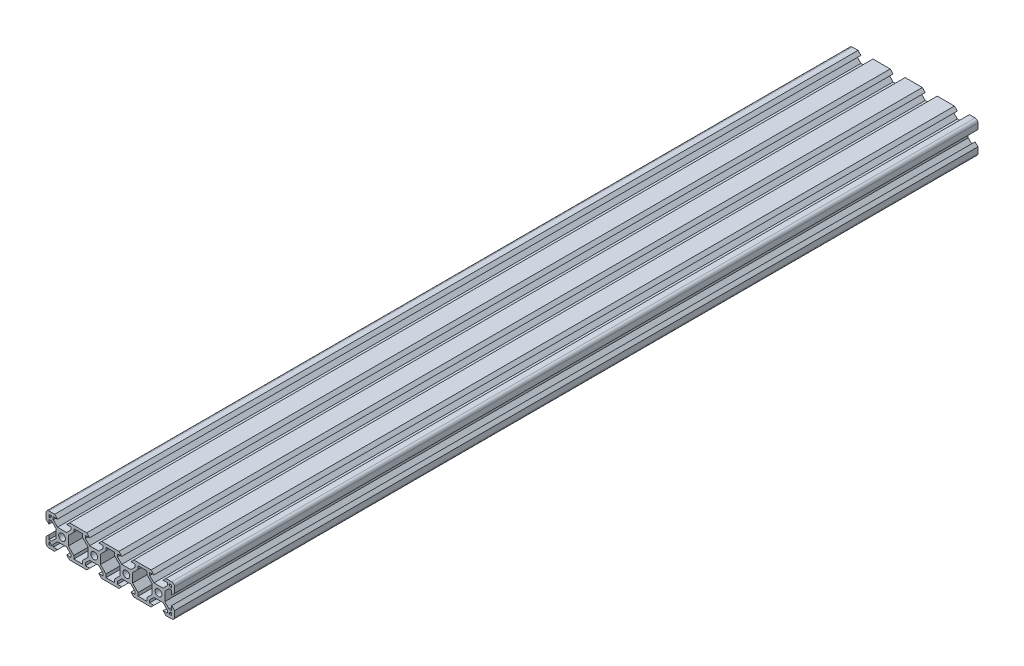
SolidWorks part; units mm, degrees
material "5052-H38, Barre (SS)"
ref_plane "Plan de face" through (0, 0, 0) normal (0, 0, 1) x (1, 0, 0)
ref_plane "Plan de dessus" through (0, 0, 0) normal (0, 1, 0) x (1, 0, 0)
ref_plane "Plan de droite" through (0, 0, 0) normal (1, 0, 0) x (0, 0, -1)
sketch "Esquisse1" plane through (0, 0, 0) normal (0, 0, 1) x (1, 0, 0)
  line L0 (0, 0) -> (0, 10) construction
  line L1 (0, 0) -> (-40, 0) construction
  line L2 (-40, 10) -> (-30, 0) construction
  line L3 (-30, 0) -> (-20, 10) construction
  line L4 (-20, 10) -> (-10, 0) construction
  line L5 (-10, 0) -> (0, 10) construction
  line L6 (-10, 0) -> (-10, 10) construction
  line L7 (-20, 10) -> (-20, 0) construction
  line L8 (-40, 0) -> (-40, 10) construction
  line L9 (-38.2, 10) -> (-34.64, 10)
  line L10 (-34.64, 10) -> (-32.84, 8.2)
  line L11 (-32.84, 8.2) -> (-35.4993, 8.2)
  line L12 (-35.4993, 8.2) -> (-35.4993, 6.56)
  line L13 (-35.4993, 6.56) -> (-32.84, 3.9007)
  line L14 (-32.84, 3.9007) -> (-27.16, 3.9007)
  line L15 (-30, 0) -> (-30, 10) construction
  line L16 (-33.9007, 2.84) -> (-33.9007, 0)
  line L17 (-36.56, 5.4993) -> (-33.9007, 2.84)
  line L18 (-38.2, 5.4993) -> (-36.56, 5.4993)
  line L19 (-38.2, 2.84) -> (-38.2, 5.4993)
  line L20 (-40, 4.64) -> (-38.2, 2.84)
  line L21 (-40, 8.2) -> (-40, 4.64)
  line L22 (-38.2, 8.2) -> (-38.2, 6.5693)
  line L23 (-38.2, 6.5693) -> (-37.63, 6.5693)
  line L24 (-37.63, 6.5693) -> (-36.5693, 7.63)
  line L25 (-36.5693, 7.63) -> (-36.5693, 8.2)
  line L26 (-36.5693, 8.2) -> (-38.2, 8.2)
  line L27 (-17.3, 6.2393) -> (-17.3, 8.2)
  line L28 (-13.9007, 2.84) -> (-17.3, 6.2393)
  line L29 (-13.9007, -2.84) -> (-13.9007, 2.84)
  line L30 (-14.64, 10) -> (-12.84, 8.2)
  line L31 (-12.84, 8.2) -> (-15.4993, 8.2)
  line L32 (-15.4993, 8.2) -> (-15.4993, 6.56)
  line L33 (-15.4993, 6.56) -> (-12.84, 3.9007)
  line L34 (-12.84, 3.9007) -> (-7.16, 3.9007)
  line L35 (-5.36, 10) -> (-7.16, 8.2)
  line L36 (-7.16, 8.2) -> (-4.5007, 8.2)
  line L37 (-4.5007, 8.2) -> (-4.5007, 6.56)
  line L38 (-4.5007, 6.56) -> (-7.16, 3.9007)
  line L39 (-5.36, 10) -> (5.36, 10)
  line L40 (-6.0993, -2.84) -> (-6.0993, 2.84)
  line L41 (-6.0993, 2.84) -> (-2.7, 6.2393)
  line L42 (-2.7, 6.2393) -> (-2.7, 8.2)
  line L43 (-2.7, 8.2) -> (2.7, 8.2)
  line L44 (-25.36, 10) -> (-27.16, 8.2)
  line L45 (-7.16, 3.9007) -> (-6.0993, 2.84) construction
  line L46 (-36.5693, -7.63) -> (-36.5693, -8.2)
  line L47 (-37.63, -6.5693) -> (-36.5693, -7.63)
  line L48 (-38.2, -6.5693) -> (-37.63, -6.5693)
  line L49 (-38.2, -8.2) -> (-38.2, -6.5693)
  line L50 (-27.16, 8.2) -> (-24.5007, 8.2)
  line L51 (-24.5007, 8.2) -> (-24.5007, 6.56)
  line L52 (-24.5007, 6.56) -> (-27.16, 3.9007)
  line L53 (-25.36, 10) -> (-14.64, 10)
  line L54 (-26.0993, -2.84) -> (-26.0993, 2.84)
  line L55 (-26.0993, 2.84) -> (-22.7, 6.2393)
  line L56 (-22.7, 6.2393) -> (-22.7, 8.2)
  line L57 (-22.7, 8.2) -> (-17.3, 8.2)
  line L58 (-27.16, 3.9007) -> (-26.0993, 2.84) construction
  line L59 (-26.0993, 2.84) -> (-26.0962, 2.8177) construction
  line L60 (-36.5693, -8.2) -> (-38.2, -8.2)
  line L61 (-26.0993, -2.84) -> (-22.7, -6.2393)
  line L62 (-22.7, -6.2393) -> (-22.7, -8.2)
  line L63 (-22.7, -8.2) -> (-17.3, -8.2)
  line L64 (-17.3, -6.2393) -> (-17.3, -8.2)
  line L65 (-13.9007, -2.84) -> (-17.3, -6.2393)
  line L66 (-2.7, -8.2) -> (2.7, -8.2)
  line L67 (-2.7, -6.2393) -> (-2.7, -8.2)
  line L68 (-6.0993, -2.84) -> (-2.7, -6.2393)
  line L69 (-5.36, -10) -> (5.36, -10)
  line L70 (-5.36, -10) -> (-7.16, -8.2)
  line L71 (-7.16, -8.2) -> (-4.5007, -8.2)
  line L72 (-4.5007, -8.2) -> (-4.5007, -6.56)
  line L73 (-4.5007, -6.56) -> (-7.16, -3.9007)
  line L74 (-12.84, -3.9007) -> (-7.16, -3.9007)
  line L75 (-15.4993, -6.56) -> (-12.84, -3.9007)
  line L76 (-15.4993, -8.2) -> (-15.4993, -6.56)
  line L77 (-12.84, -8.2) -> (-15.4993, -8.2)
  line L78 (-14.64, -10) -> (-12.84, -8.2)
  line L79 (-25.36, -10) -> (-14.64, -10)
  line L80 (-25.36, -10) -> (-27.16, -8.2)
  line L81 (-27.16, -8.2) -> (-24.5007, -8.2)
  line L82 (-24.5007, -8.2) -> (-24.5007, -6.56)
  line L83 (-24.5007, -6.56) -> (-27.16, -3.9007)
  line L84 (-32.84, -3.9007) -> (-27.16, -3.9007)
  line L85 (-35.4993, -6.56) -> (-32.84, -3.9007)
  line L86 (-35.4993, -8.2) -> (-35.4993, -6.56)
  line L87 (-32.84, -8.2) -> (-35.4993, -8.2)
  line L88 (-34.64, -10) -> (-32.84, -8.2)
  line L89 (-38.2, -10) -> (-34.64, -10)
  line L90 (-40, -8.2) -> (-40, -4.64)
  line L91 (-40, -4.64) -> (-38.2, -2.84)
  line L92 (-38.2, -2.84) -> (-38.2, -5.4993)
  line L93 (-38.2, -5.4993) -> (-36.56, -5.4993)
  line L94 (-36.56, -5.4993) -> (-33.9007, -2.84)
  line L95 (-33.9007, -2.84) -> (-33.9007, 0)
  line L96 (36.5693, 8.2) -> (38.2, 8.2)
  line L97 (36.5693, 7.63) -> (36.5693, 8.2)
  line L98 (37.63, 6.5693) -> (36.5693, 7.63)
  line L99 (38.2, 6.5693) -> (37.63, 6.5693)
  line L100 (38.2, 8.2) -> (38.2, 6.5693)
  line L101 (36.5693, -8.2) -> (38.2, -8.2)
  line L102 (36.5693, -7.63) -> (36.5693, -8.2)
  line L103 (37.63, -6.5693) -> (36.5693, -7.63)
  line L104 (38.2, -6.5693) -> (37.63, -6.5693)
  line L105 (38.2, -8.2) -> (38.2, -6.5693)
  line L106 (13.9007, -2.84) -> (17.3, -6.2393)
  line L107 (17.3, -6.2393) -> (17.3, -8.2)
  line L108 (22.7, -8.2) -> (17.3, -8.2)
  line L109 (22.7, -6.2393) -> (22.7, -8.2)
  line L110 (26.0993, -2.84) -> (22.7, -6.2393)
  line L111 (26.0993, -2.84) -> (26.0993, 2.84)
  line L112 (26.0993, 2.84) -> (22.7, 6.2393)
  line L113 (22.7, 6.2393) -> (22.7, 8.2)
  line L114 (22.7, 8.2) -> (17.3, 8.2)
  line L115 (17.3, 6.2393) -> (17.3, 8.2)
  line L116 (13.9007, 2.84) -> (17.3, 6.2393)
  line L117 (13.9007, -2.84) -> (13.9007, 2.84)
  line L118 (2.7, -6.2393) -> (2.7, -8.2)
  line L119 (6.0993, -2.84) -> (2.7, -6.2393)
  line L120 (6.0993, -2.84) -> (6.0993, 2.84)
  line L121 (6.0993, 2.84) -> (2.7, 6.2393)
  line L122 (2.7, 6.2393) -> (2.7, 8.2)
  line L123 (5.36, -10) -> (7.16, -8.2)
  line L124 (7.16, -8.2) -> (4.5007, -8.2)
  line L125 (4.5007, -8.2) -> (4.5007, -6.56)
  line L126 (4.5007, -6.56) -> (7.16, -3.9007)
  line L127 (12.84, -3.9007) -> (7.16, -3.9007)
  line L128 (15.4993, -6.56) -> (12.84, -3.9007)
  line L129 (15.4993, -8.2) -> (15.4993, -6.56)
  line L130 (12.84, -8.2) -> (15.4993, -8.2)
  line L131 (14.64, -10) -> (12.84, -8.2)
  line L132 (25.36, -10) -> (14.64, -10)
  line L133 (25.36, -10) -> (27.16, -8.2)
  line L134 (27.16, -8.2) -> (24.5007, -8.2)
  line L135 (24.5007, -8.2) -> (24.5007, -6.56)
  line L136 (24.5007, -6.56) -> (27.16, -3.9007)
  line L137 (32.84, -3.9007) -> (27.16, -3.9007)
  line L138 (35.4993, -6.56) -> (32.84, -3.9007)
  line L139 (35.4993, -8.2) -> (35.4993, -6.56)
  line L140 (32.84, -8.2) -> (35.4993, -8.2)
  line L141 (34.64, -10) -> (32.84, -8.2)
  line L142 (38.2, -10) -> (34.64, -10)
  line L143 (40, -8.2) -> (40, -4.64)
  line L144 (40, -4.64) -> (38.2, -2.84)
  line L145 (38.2, -2.84) -> (38.2, -5.4993)
  line L146 (38.2, -5.4993) -> (36.56, -5.4993)
  line L147 (36.56, -5.4993) -> (33.9007, -2.84)
  line L148 (33.9007, -2.84) -> (33.9007, 0)
  line L149 (33.9007, 2.84) -> (33.9007, 0)
  line L150 (36.56, 5.4993) -> (33.9007, 2.84)
  line L151 (38.2, 5.4993) -> (36.56, 5.4993)
  line L152 (38.2, 2.84) -> (38.2, 5.4993)
  line L153 (40, 4.64) -> (38.2, 2.84)
  line L154 (40, 8.2) -> (40, 4.64)
  line L155 (38.2, 10) -> (34.64, 10)
  line L156 (34.64, 10) -> (32.84, 8.2)
  line L157 (32.84, 8.2) -> (35.4993, 8.2)
  line L158 (35.4993, 8.2) -> (35.4993, 6.56)
  line L159 (35.4993, 6.56) -> (32.84, 3.9007)
  line L160 (32.84, 3.9007) -> (27.16, 3.9007)
  line L161 (24.5007, 6.56) -> (27.16, 3.9007)
  line L162 (24.5007, 8.2) -> (24.5007, 6.56)
  line L163 (27.16, 8.2) -> (24.5007, 8.2)
  line L164 (25.36, 10) -> (27.16, 8.2)
  line L165 (25.36, 10) -> (14.64, 10)
  line L166 (14.64, 10) -> (12.84, 8.2)
  line L167 (12.84, 8.2) -> (15.4993, 8.2)
  line L168 (15.4993, 8.2) -> (15.4993, 6.56)
  line L169 (15.4993, 6.56) -> (12.84, 3.9007)
  line L170 (12.84, 3.9007) -> (7.16, 3.9007)
  line L171 (4.5007, 6.56) -> (7.16, 3.9007)
  line L172 (4.5007, 8.2) -> (4.5007, 6.56)
  line L173 (7.16, 8.2) -> (4.5007, 8.2)
  line L174 (5.36, 10) -> (7.16, 8.2)
  circle A0 centre (-30, 0) radius 2.1
  circle A1 centre (-10, 0) radius 2.1
  arc A2 (-38.2, 10) -> (-40, 8.2) centre (-38.2, 8.2) ccw
  arc A3 (-38.2, -10) -> (-40, -8.2) centre (-38.2, -8.2) cw
  circle A4 centre (30, 0) radius 2.1
  circle A5 centre (10, 0) radius 2.1
  arc A6 (38.2, -10) -> (40, -8.2) centre (38.2, -8.2) ccw
  arc A7 (38.2, 10) -> (40, 8.2) centre (38.2, 8.2) cw
  point P21 (-37.0997, 7.0997)
  point P36 (-20, 8.2)
  point P47 (-10, 3.9007)
  point P54 (-6.6297, 3.3703)
  point P61 (-30, 3.9007)
  point P71 (-26.0993, 0)
  point P76 (-13.9007, 0)
  point P80 (-6.0993, 0)
  point P135 (0, -8.2)
  point P140 (0, 8.2)
  point P141 (0, -10)
  dimension "D3" = 4.2
  dimension "D4" = 4.2
  dimension "D1" = 40
  dimension "D2" = 10
  dimension "D5" = 5.68
  dimension "D6" = 1.5
  dimension "D7" = 1.64
  dimension "D8" = 1.8
  dimension "D9" = 1.07
  dimension "D11" = 5.4
extrude "Boss.-Extru.1" add sketch "Esquisse1" along normal mid plane 500
